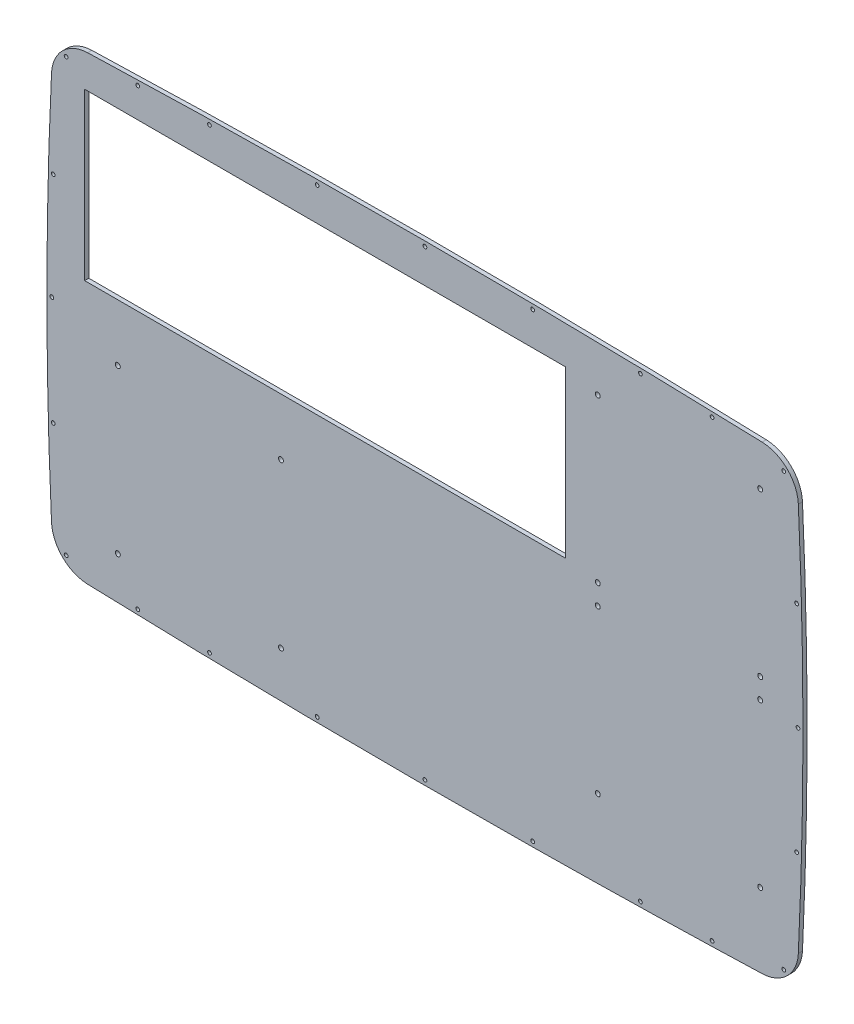
SolidWorks part; units mm, degrees
ref_plane "Front" through (0, 0, 0) normal (0, 0, 1) x (1, 0, 0)
ref_plane "Top" through (0, 0, 0) normal (0, 1, 0) x (1, 0, 0)
ref_plane "Right" through (0, 0, 0) normal (1, 0, 0) x (0, 0, -1)
sketch "Sketch1" plane through (0, 0, 0) normal (0, 0, 1) x (1, 0, 0)
  line L0 (79.622, -180.7786) -> (85.5592, -180.7149)
  line L1 (223.1034, -177.9577) -> (258.4236, -176.8528)
  circle A0 centre (-274.9542, -165.9116) radius 1.435
  arc A93 (-279.7814, -166.2105) -> (-275.1845, -170.7425) centre (-257.4604, -148.1676) ccw
  arc A94 (275.1845, -170.7425) -> (279.7814, -166.2105) centre (257.4604, -148.1676) ccw
  circle A100 centre (-274.9542, 164.9337) radius 1.4351
  circle A101 centre (-284.8103, 82.061) radius 1.4351
  circle A102 centre (-285.9024, 0) radius 1.4351
  circle A103 centre (-284.8103, -83.0389) radius 1.4351
  arc A104 (-258.4236, -176.8528) -> (-223.1034, -177.9577) centre (0, 7519.4009) ccw
  circle A105 centre (-220.0271, -174.2607) radius 1.4351
  circle A106 centre (-165.1, -175.6347) radius 1.4351
  arc A107 (-162.2131, -179.4816) -> (-85.5592, -180.7149) centre (0, 7519.4009) ccw
  arc A108 (-168.1492, -179.3542) -> (-162.2131, -179.4816) centre (0, 7519.4009) ccw
  circle A109 centre (-82.55, -176.963) radius 1.4351
  circle A110 centre (0, -177.4057) radius 1.4351
  circle A111 centre (82.55, -176.963) radius 1.4351
  circle A112 centre (165.1, -175.6347) radius 1.4351
  circle A113 centre (220.0271, -174.2607) radius 1.4351
  circle A114 centre (284.8103, -83.0389) radius 1.4351
  circle A115 centre (285.9024, 0) radius 1.4351
  circle A116 centre (284.8103, 82.061) radius 1.4351
  circle A117 centre (274.9542, 164.9337) radius 1.4351
  circle A118 centre (220.0271, 173.2828) radius 1.4351
  circle A119 centre (165.1, 174.6568) radius 1.4351
  circle A120 centre (82.55, 175.9851) radius 1.4351
  circle A121 centre (0, 176.4278) radius 1.4351
  circle A122 centre (-82.55, 175.9851) radius 1.4351
  circle A123 centre (-220.0271, 173.2828) radius 1.4351
  circle A124 centre (-165.1, 174.6568) radius 1.4351
  arc A125 (-162.2131, 178.5037) -> (-168.1492, 178.3763) centre (0, -7520.3788) ccw
  arc A126 (-85.5592, 179.737) -> (-162.2131, 178.5037) centre (0, -7520.3788) ccw
  arc A127 (-79.622, 179.8007) -> (-85.5592, 179.737) centre (0, -7520.3788) ccw
  arc A128 (-2.9688, 180.2118) -> (-79.622, 179.8007) centre (0, -7520.3788) ccw
  arc A129 (2.9688, 180.2118) -> (-2.9688, 180.2118) centre (0, -7520.3788) ccw
  arc A130 (79.622, 179.8007) -> (2.9688, 180.2118) centre (0, -7520.3788) ccw
  arc A131 (85.5592, 179.737) -> (79.622, 179.8007) centre (0, -7520.3788) ccw
  arc A132 (162.2131, 178.5037) -> (85.5592, 179.737) centre (0, -7520.3788) ccw
  arc A133 (168.1492, 178.3763) -> (162.2131, 178.5037) centre (0, -7520.3788) ccw
  arc A134 (217.1671, 177.1496) -> (168.1492, 178.3763) centre (0, -7520.3788) ccw
  arc A135 (223.1034, 176.9798) -> (217.1671, 177.1496) centre (0, -7520.3788) ccw
  arc A136 (258.4236, 175.8749) -> (223.1034, 176.9798) centre (0, -7520.3788) ccw
  arc A137 (275.1845, 169.7646) -> (258.4236, 175.8749) centre (257.4604, 147.1897) ccw
  arc A138 (279.7814, 165.2326) -> (275.1845, 169.7646) centre (257.4604, 147.1897) ccw
  arc A139 (286.1291, 148.559) -> (279.7814, 165.2326) centre (257.4604, 147.1897) ccw
  arc A140 (288.513, 85.1308) -> (286.1291, 148.559) centre (-2834.64, -0.4889) ccw
  arc A141 (288.6701, 79.1915) -> (288.513, 85.1308) centre (-2834.64, -0.4889) ccw
  arc A142 (289.6845, 2.9713) -> (288.6701, 79.1915) centre (-2834.64, -0.4889) ccw
  arc A143 (289.6854, -2.9701) -> (289.6845, 2.9713) centre (-2834.64, -0.4889) ccw
  arc A144 (288.6701, -80.1694) -> (289.6854, -2.9701) centre (-2834.64, -0.4889) ccw
  arc A145 (288.513, -86.1087) -> (288.6701, -80.1694) centre (-2834.64, -0.4889) ccw
  arc A146 (286.1291, -149.5369) -> (288.513, -86.1087) centre (-2834.64, -0.4889) ccw
  arc A147 (279.7814, -166.2105) -> (286.1291, -149.5369) centre (257.4604, -148.1676) ccw
  arc A148 (275.1845, -170.7425) -> (279.7814, -166.2105) centre (257.4604, -148.1676) ccw
  arc A149 (258.4236, -176.8528) -> (275.1845, -170.7425) centre (257.4604, -148.1676) ccw
  arc A150 (217.1671, -178.1275) -> (223.1034, -177.9577) centre (0, 7519.4009) ccw
  arc A151 (168.1492, -179.3542) -> (217.1671, -178.1275) centre (0, 7519.4009) ccw
  arc A152 (85.5592, -180.7149) -> (162.2131, -179.4816) centre (0, 7519.4009) ccw
  arc A153 (162.2131, -179.4816) -> (168.1492, -179.3542) centre (0, 7519.4009) ccw
  arc A154 (2.9688, -181.1897) -> (79.622, -180.7786) centre (0, 7519.4009) ccw
  arc A155 (-2.9688, -181.1897) -> (2.9688, -181.1897) centre (0, 7519.4009) ccw
  arc A156 (-79.622, -180.7786) -> (-2.9688, -181.1897) centre (0, 7519.4009) ccw
  arc A157 (-85.5592, -180.7149) -> (-79.622, -180.7786) centre (0, 7519.4009) ccw
  arc A158 (-217.1671, -178.1275) -> (-168.1492, -179.3542) centre (0, 7519.4009) ccw
  arc A159 (-223.1034, -177.9577) -> (-217.1671, -178.1275) centre (0, 7519.4009) ccw
  arc A160 (-275.1845, -170.7425) -> (-258.4236, -176.8528) centre (-257.4604, -148.1676) ccw
  arc A161 (-279.7814, -166.2105) -> (-275.1845, -170.7425) centre (-257.4604, -148.1676) ccw
  arc A162 (-286.1291, -149.5369) -> (-279.7814, -166.2105) centre (-257.4604, -148.1676) ccw
  arc A163 (-288.513, -86.1087) -> (-286.1291, -149.5369) centre (2834.64, -0.4889) ccw
  arc A164 (-288.6701, -80.1694) -> (-288.513, -86.1087) centre (2834.64, -0.4889) ccw
  arc A165 (-289.6854, -2.9701) -> (-288.6701, -80.1694) centre (2834.64, -0.4889) ccw
  arc A166 (-289.6845, 2.9713) -> (-289.6854, -2.9701) centre (2834.64, -0.4889) ccw
  arc A167 (-288.6701, 79.1915) -> (-289.6845, 2.9713) centre (2834.64, -0.4889) ccw
  arc A168 (-288.513, 85.1308) -> (-288.6701, 79.1915) centre (2834.64, -0.4889) ccw
  arc A169 (-286.1291, 148.559) -> (-288.513, 85.1308) centre (2834.64, -0.4889) ccw
  arc A170 (-279.7814, 165.2326) -> (-286.1291, 148.559) centre (-257.4604, 147.1897) ccw
  arc A171 (-275.1845, 169.7646) -> (-279.7814, 165.2326) centre (-257.4604, 147.1897) ccw
  arc A172 (-258.4236, 175.8749) -> (-275.1845, 169.7646) centre (-257.4604, 147.1897) ccw
  arc A173 (-223.1034, 176.9798) -> (-258.4236, 175.8749) centre (0, -7520.3788) ccw
  arc A174 (-217.1671, 177.1496) -> (-223.1034, 176.9798) centre (0, -7520.3788) ccw
  arc A175 (-168.1492, 178.3763) -> (-217.1671, 177.1496) centre (0, -7520.3788) ccw
  circle A176 centre (274.9542, -165.9116) radius 1.4351
extrude "Boss-Extrude1" add sketch "Sketch1" along normal blind 3.175
sketch "Sketch2" plane through (0, 0, 3.175) normal (0, 0, 1) x (1, 0, 0)
  line L0 (-260.7291, 150.4749) -> (-260.7291, 23.4749)
  line L1 (107.5709, 23.4749) -> (-260.7291, 23.4749)
  line L2 (107.5709, 23.4749) -> (107.5709, 150.4749)
  line L3 (107.5709, 150.4749) -> (-260.7291, 150.4749)
  arc A0 (258.4236, 175.8749) -> (-258.4236, 175.8749) centre (0, -7520.3788) ccw construction
  arc A1 (258.4236, 175.8749) -> (-258.4236, 175.8749) centre (0, -7520.3788) ccw
  dimension "D2" = 25.4
  dimension "D1" = 25.4
  dimension "D3" = 127
  dimension "D4" = 368.3
extrude "Cut-Extrude1" cut sketch "Sketch2" against normal through all contours L2 L3 L0 L1
sketch "Sketch4" plane through (0, 0, 0) normal (0, 0, -1) x (-1, 0, 0)
  circle A0 centre (-256.9191, 144.1249) radius 1.8987
  circle A1 centre (-132.4191, 144.1249) radius 1.8987
  circle A2 centre (-256.9191, 19.6249) radius 1.8987
  circle A3 centre (-256.9191, 4.1249) radius 1.8987
  circle A4 centre (-132.4191, 19.6249) radius 1.8987
  circle A5 centre (-132.4191, 4.1249) radius 1.8987
  circle A6 centre (-256.9191, -120.3751) radius 1.8987
  circle A7 centre (-132.4191, -120.3751) radius 1.8987
  point P16 (0, 0)
  point P17 (0, 0)
  point P18 (-65.179, -108.4845)
  point P19 (0, 0)
  point P20 (0, 0)
  point P21 (0, 0)
  point P22 (0, 0)
  point P23 (0, 0)
  point P24 (-246.5928, 116.4118)
  point P25 (-250.4012, 131.6453)
  point P26 (0, 0)
  point P27 (-254.5549, 143.7943)
  point P28 (-256.938, 143.8116)
  point P31 (-257.4604, 144.1249)
  point P32 (-256.9191, 144.1249)
  dimension "D7" = 3.7973
  dimension "D1" = 124.5
  dimension "D2" = 124.5
  dimension "D3" = 140
  dimension "D4" = 264.5
  dimension "D5" = 29.21
  dimension "D6" = 31.75
extrude "Cut-Extrude2" cut sketch "Sketch4" against normal through all
sketch "Sketch5" plane through (0, 0, 0) normal (0, 0, -1) x (-1, 0, 0)
  circle A0 centre (235.3291, -145.1028) radius 1.8987
  circle A1 centre (110.3291, -145.1028) radius 1.8987
  circle A2 centre (110.3291, -20.1028) radius 1.8987
  circle A3 centre (235.3291, -20.1028) radius 1.8987
  point P8 (0, 0)
  point P9 (0, 0)
  point P10 (0, 0)
  point P11 (0, 0)
  point P12 (0, 0)
  point P13 (0, 0)
  point P14 (233.2646, -146.7593)
  dimension "D1" = 3.7973
  dimension "D4" = 50.8
  dimension "D2" = 125
  dimension "D3" = 125
  dimension "D5" = 31.75
extrude "Cut-Extrude3" cut sketch "Sketch5" against normal through all
